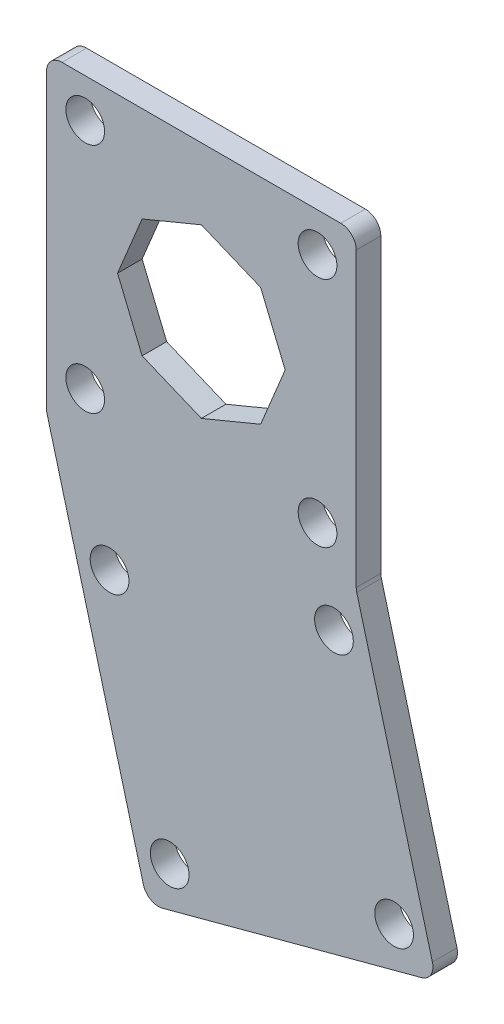
SolidWorks part; units mm, degrees
ref_plane "Front Plane" through (0, 0, 0) normal (0, 0, 1) x (1, 0, 0)
ref_plane "Top Plane" through (0, 0, 0) normal (0, 1, 0) x (1, 0, 0)
ref_plane "Right Plane" through (0, 0, 0) normal (1, 0, 0) x (0, 0, -1)
sketch "Sketch1" plane through (0, 0, 0) normal (0, 0, 1) x (1, 0, 0)
  line L0 (-20, 20) -> (20, -20) construction
  line L1 (-20, 20) -> (20, 20)
  line L2 (-20, 20) -> (-20, -20)
  line L3 (-20, -20) -> (20, -20) construction
  line L4 (20, 20) -> (20, -20)
  line L5 (-20, 0) -> (-15, 0) construction
  line L6 (-15, 15) -> (-15, -15) construction
  line L7 (15, 0) -> (20, 0) construction
  line L8 (15, 15) -> (15, -15) construction
  line L9 (-6.9677, -68.637) -> (30.3528, -58.637)
  line L10 (-20, -20) -> (-6.9677, -68.637)
  line L11 (20, -20) -> (30.3528, -58.637)
  line L12 (10.3984, -58.8074) -> (11.6925, -63.637) construction
  line L14 (10.8239, 0) -> (7.6537, 7.6537)
  line L15 (-11.855, -33.7119) -> (17.1227, -25.9473) construction
  line L16 (-11.855, -33.7119) -> (-4.0905, -62.6897) construction
  line L17 (-4.0905, -62.6897) -> (24.8873, -54.9251) construction
  line L18 (17.1227, -25.9473) -> (24.8873, -54.9251) construction
  line L19 (7.6537, 7.6537) -> (0, 10.8239)
  line L20 (0, 10.8239) -> (-7.6537, 7.6537)
  line L21 (-7.6537, 7.6537) -> (-10.8239, 0)
  line L22 (-10.8239, 0) -> (-7.6537, -7.6537)
  line L23 (-7.6537, -7.6537) -> (0, -10.8239)
  line L24 (0, -10.8239) -> (7.6537, -7.6537)
  line L25 (7.6537, -7.6537) -> (10.8239, 0)
  circle A0 centre (-15, 15) radius 2.5
  circle A1 centre (-15, -15) radius 2.5
  circle A2 centre (15, 15) radius 2.5
  circle A3 centre (15, -15) radius 2.5
  circle A4 centre (-11.855, -33.7119) radius 2.5
  circle A5 centre (17.1227, -25.9473) radius 2.5
  circle A6 centre (24.8873, -54.9251) radius 2.5
  circle A7 centre (-4.0905, -62.6897) radius 2.5
  circle A8 centre (0, 0) radius 10 construction
  point P4 (0, 0)
  point P11 (-20, 0)
  point P12 (-15, 0)
  point P19 (20, 0)
  point P20 (15, 0)
  point P27 (11.6925, -63.637)
  point P28 (10.3984, -58.8074)
  dimension "D7" = 5
  dimension "D8" = 5
  dimension "D9" = 5
  dimension "D10" = 5
  dimension "D22" = 5
  dimension "D23" = 5
  dimension "D24" = 5
  dimension "D25" = 5
  dimension "D26" = 20
  dimension "D1" = 40
  dimension "D2" = 40
  dimension "D3" = 5
  dimension "D4" = 30
  dimension "D5" = 30
  dimension "D6" = 5
  dimension "D11" = 40
  dimension "D12" = 75
  dimension "D13" = 75
  dimension "D14" = 90
  dimension "D15" = 5
  dimension "D16" = 90
  dimension "D17" = 30
  dimension "D18" = 30
  dimension "D19" = 270
  dimension "D20" = 270
  dimension "D21" = 90
extrude "Boss-Extrude1" add sketch "Sketch1" along normal blind 3.175
fillet "Fillet1" radius 2 6 edges at (30.3528, -58.637, 1.5875) (-6.9677, -68.637, 1.5875) (-20, -20, 1.5875) (20, -20, 1.5875) (20, 20, 1.5875) (-20, 20, 1.5875)
